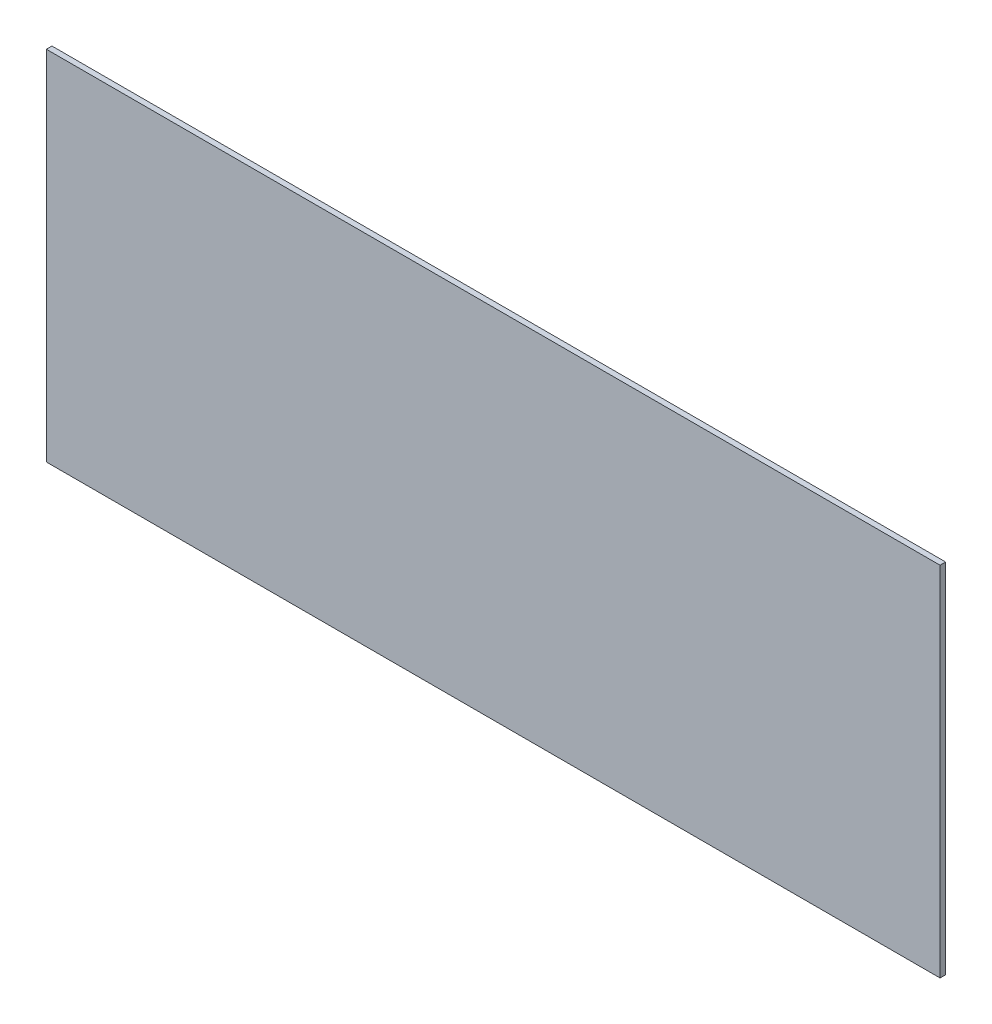
SolidWorks part; units mm, degrees
material "Rubber"
ref_plane "Front" through (0, 0, 0) normal (0, 0, 1) x (1, 0, 0)
ref_plane "Top" through (0, 0, 0) normal (0, 1, 0) x (1, 0, 0)
ref_plane "Right" through (0, 0, 0) normal (1, 0, 0) x (0, 0, -1)
sketch "Sketch1" plane through (0, 0, 0) normal (0, 0, 1) x (1, 0, 0)
  line L1 (-63.5, 25.4) -> (63.5, 25.4)
  line L2 (-63.5, 25.4) -> (-63.5, -25.4)
  line L3 (-63.5, -25.4) -> (63.5, -25.4)
  line L4 (63.5, 25.4) -> (63.5, -25.4)
  line L5 (-63.5, 25.4) -> (63.5, -25.4) construction
  line L6 (-63.5, -25.4) -> (63.5, 25.4) construction
  point P0 (0, 0)
  dimension "D1" = 127
  dimension "D2" = 50.8
extrude "Boss-Extrude1" add sketch "Sketch1" along normal blind 0.7937
